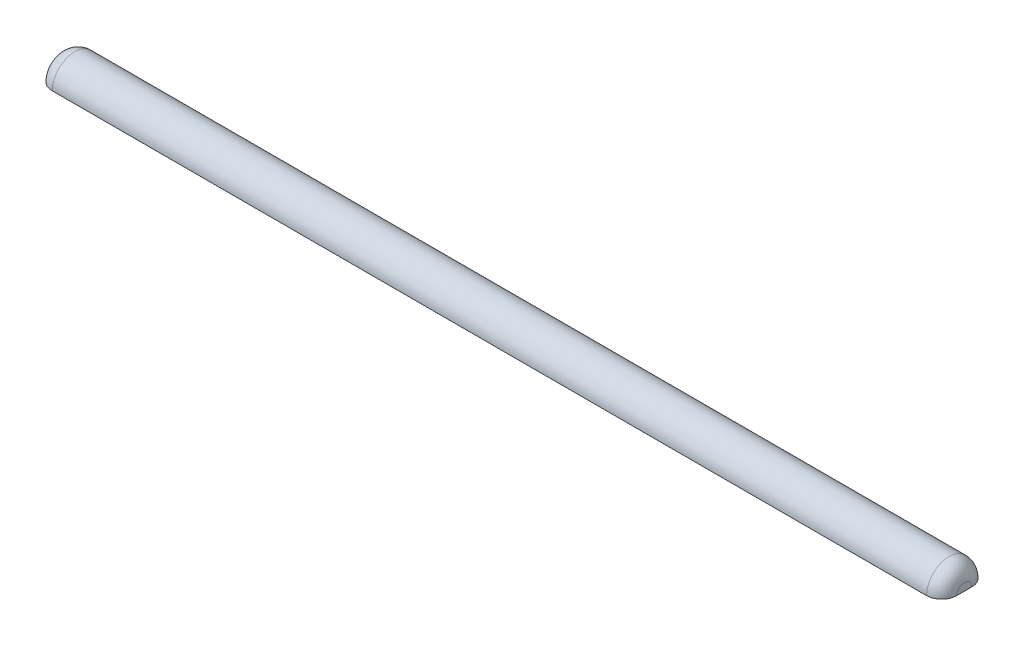
SolidWorks part; units mm, degrees
ref_plane "Front Plane" through (0, 0, 0) normal (0, 0, 1) x (1, 0, 0)
ref_plane "Top Plane" through (0, 0, 0) normal (0, 1, 0) x (1, 0, 0)
ref_plane "Right Plane" through (0, 0, 0) normal (1, 0, 0) x (0, 0, -1)
sketch "Sketch1" plane through (0, 0, 0) normal (1, 0, 0) x (0, 0, -1)
  line L0 (0, 0) -> (0.15, 0)
  arc A0 (0, 0) -> (0.15, 0) centre (0.075, 0) cw
  dimension "D1" = 0.15
extrude "Boss-Extrude1" add sketch "Sketch1" along normal blind 3
fillet "Fillet1" radius 0.05 2 edges at (3, 0.075, -0.075) (0, 0.075, -0.075)
